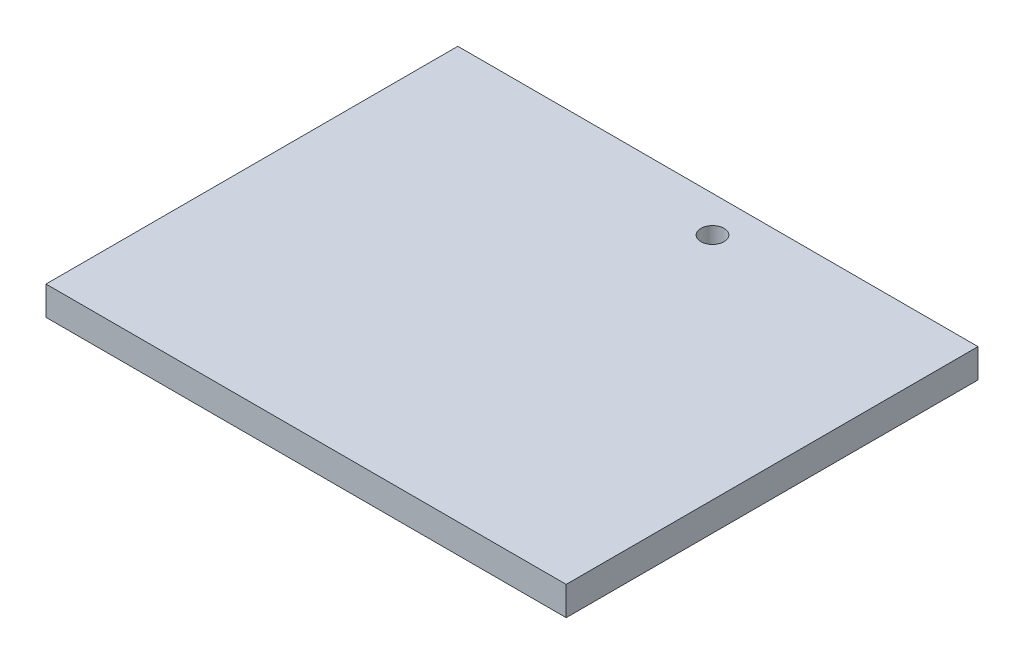
SolidWorks part; units mm, degrees
ref_plane "Front Plane" through (0, 0, 0) normal (0, 0, 1) x (1, 0, 0)
ref_plane "Top Plane" through (0, 0, 0) normal (0, 1, 0) x (1, 0, 0)
ref_plane "Right Plane" through (0, 0, 0) normal (1, 0, 0) x (0, 0, -1)
sketch "Sketch1" plane through (0, 0, 0) normal (0, 1, 0) x (1, 0, 0)
  line L0 (36, 28.5) -> (4.25, 28.5)
  line L1 (-36, 28.5) -> (36, 28.5)
  line L2 (-36, 28.5) -> (-36, -28.5)
  line L3 (-36, -28.5) -> (36, -28.5)
  line L4 (36, 28.5) -> (36, -28.5)
  line L5 (-36, 28.5) -> (36, -28.5) construction
  line L6 (-36, -28.5) -> (36, 28.5) construction
  line L7 (4.25, 28.5) -> (4.25, 23.5) construction
  circle A0 centre (4.25, 23.5) radius 1.6
  point P0 (0, 0)
  dimension "D5" = 3.2
  dimension "D1" = 72
  dimension "D2" = 57
  dimension "D3" = 31.75
  dimension "D4" = 5
extrude "Boss-Extrude1" add sketch "Sketch1" along normal blind 4 contours L4 L0 L1 L2 L3 A0
